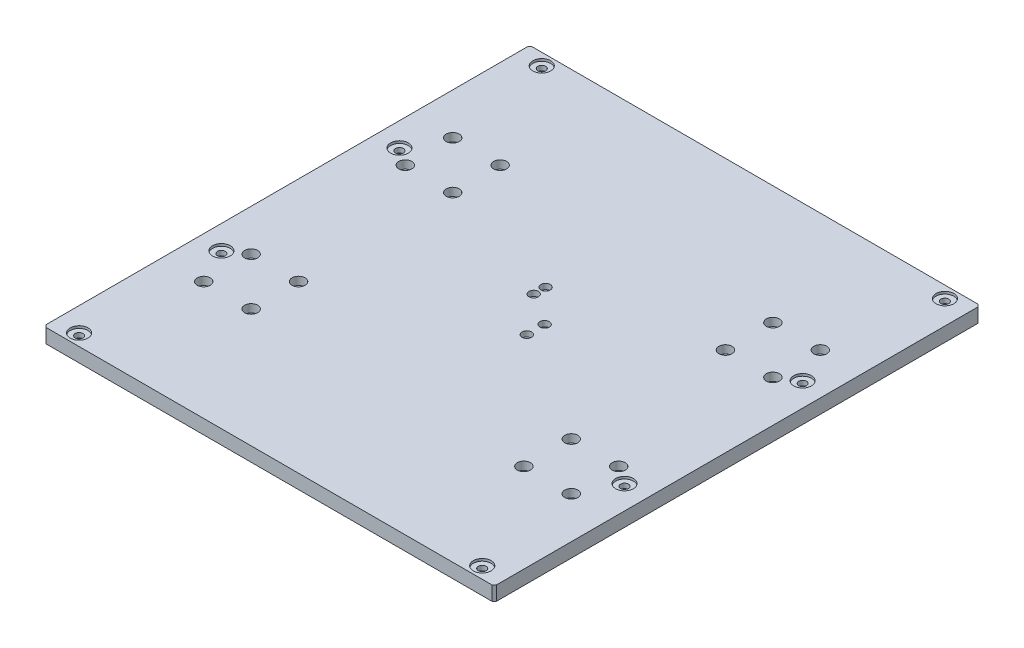
SolidWorks part; units mm, degrees
material "电木板A级"
ref_plane "前视" through (0, 0, 0) normal (0, 0, 1) x (1, 0, 0)
ref_plane "上视" through (0, 0, 0) normal (0, 1, 0) x (1, 0, 0)
ref_plane "右视" through (0, 0, 0) normal (1, 0, 0) x (0, 0, -1)
sketch "草图1" plane through (0, 0, 0) normal (0, 1, 0) x (1, 0, 0)
  line L1 (-190, -205) -> (190, -205)
  line L2 (-190, -205) -> (-190, 205)
  line L3 (-190, 205) -> (190, 205)
  line L4 (190, -205) -> (190, 205)
  line L5 (-190, -205) -> (190, 205) construction
  line L6 (-190, 205) -> (190, -205) construction
  point P0 (0, 0)
  dimension "D1" = 380
  dimension "D2" = 410
extrude "凸台-拉伸1" add sketch "草图1" along normal blind 12
hole_wizard "打孔尺寸根据内六角圆柱头螺钉的类型3" positions "草图3" profile "草图2" counterbore size "M6" standard "Gb" end condition through all
sketch "草图3" plane through (0, 12, 0) normal (0, 1, 0) x (1, 0, 0)
  line L0 (0, -205) -> (0, 0) construction
  line L1 (-190, -205) -> (190, -205) construction
  line L2 (0, 0) -> (190, 0) construction
  line L3 (190, -205) -> (190, 205) construction
  point P20 (-115, 65)
  point P21 (-115, 105)
  point P22 (-155, 105)
  point P23 (-155, 65)
  point P35 (155, 65)
  point P36 (155, 105)
  point P37 (115, 105)
  point P38 (115, 65)
  point P39 (115, -65)
  point P40 (115, -105)
  point P41 (155, -105)
  point P42 (155, -65)
  point P43 (-155, -65)
  point P44 (-155, -105)
  point P45 (-115, -105)
  point P46 (-115, -65)
  dimension "D1" = 40
  dimension "D2" = 40
  dimension "D3" = 270
  dimension "D4" = 130
sketch "草图2" plane through (-115, 12, -65) normal (1, 0, 0) x (0, 0, 1)
  line L0 (0, 0) -> (0, 12)
  line L1 (0, 12) -> (3.3, 12)
  line L3 (3.3, 12) -> (3.3, 6.8)
  line L4 (3.3, 6.8) -> (5.5, 6.8)
  line L5 (5.5, 6.8) -> (5.5, 0)
  line L7 (5.5, 0) -> (0, 0)
  line L11 (0, -6.35) -> (0, 107.95) construction
  dimension "通孔孔直径" = 6.6
  dimension "通孔孔深度" = 12
  dimension "柱形沉头孔直径" = 11
  dimension "柱形沉头孔深度" = 6.8
hole_wizard "打孔尺寸根据内六角圆柱头螺钉的类型3" positions "草图5" profile "草图4" counterbore size "M4" standard "Gb" end condition through all
sketch "草图5" plane through (0, 12, 0) normal (0, 1, 0) x (1, 0, 0)
  line L0 (38.9, 0) -> (190, 0) construction
  line L2 (-190, -205) -> (190, -205) construction
  line L3 (190, -205) -> (190, 205) construction
  line L4 (-190, -205) -> (190, -205) construction
  line L5 (190, -205) -> (190, 205) construction
  point P0 (20, 7.5)
  point P8 (20, -7.5)
  point P9 (0, -205)
  point P14 (190, 0)
  point P17 (-6.7, 25)
  point P21 (-6.7, 35)
  point P24 (0, -205)
  dimension "D1" = 15
  dimension "D2" = 20
  dimension "D3" = 25
  dimension "D4" = 6.7
  dimension "D5" = 10
sketch "草图4" plane through (20, 12, -7.5) normal (1, 0, 0) x (0, 0, 1)
  line L0 (0, 0) -> (0, 12)
  line L1 (0, 12) -> (2.25, 12)
  line L3 (2.25, 12) -> (2.25, 4.6)
  line L4 (2.25, 4.6) -> (4, 4.6)
  line L5 (4, 4.6) -> (4, 0)
  line L7 (4, 0) -> (0, 0)
  line L11 (0, -6.35) -> (0, 107.95) construction
  dimension "通孔孔直径" = 4.5
  dimension "通孔孔深度" = 12
  dimension "柱形沉头孔直径" = 8
  dimension "柱形沉头孔深度" = 4.6
hole_wizard "打孔尺寸根据内六角圆柱头螺钉的类型3" positions "草图9" profile "草图8" counterbore size "M6" standard "Gb" end condition through all
sketch "草图9" plane through (-174.7145, 0, 28.6293) normal (0, 1, 0) x (1, 0, 0)
  line L0 (174.7145, -176.3707) -> (174.7145, 28.6293) construction
  line L1 (-15.2855, -176.3707) -> (364.7145, -176.3707) construction
  line L2 (174.7145, 28.6293) -> (-15.2855, 28.6293) construction
  line L3 (-15.2855, 233.6293) -> (-15.2855, -176.3707) construction
  point P0 (4.7145, 223.7293)
  point P2 (4.7145, 103.7293)
  point P17 (344.7145, 103.7293)
  point P18 (344.7145, 223.7293)
  point P21 (344.7145, -166.4707)
  point P22 (344.7145, -46.4707)
  point P23 (4.7145, -46.4707)
  point P24 (4.7145, -166.4707)
  dimension "D1" = 340
  dimension "D2" = 120
  dimension "D3" = 150.2
sketch "草图8" plane through (-170, 0, -195.1) normal (1, 0, 0) x (0, 0, -1)
  line L0 (0, 0) -> (0, 12)
  line L1 (0, 12) -> (3.3, 12)
  line L3 (3.3, 12) -> (3.3, 6)
  line L4 (3.3, 6) -> (5.5, 6)
  line L5 (5.5, 6) -> (5.5, 0)
  line L7 (5.5, 0) -> (0, 0)
  line L11 (0, -6.35) -> (0, 107.95) construction
  dimension "通孔孔直径" = 6.6
  dimension "通孔孔深度" = 12
  dimension "柱形沉头孔直径" = 11
  dimension "柱形沉头孔深度" = 6
hole_wizard "孔1" positions "草图12" profile "草图11" legacy
sketch "草图12" plane through (0, 12, 0) normal (0, 1, 0) x (1, 0, 0)
  line L0 (0, 205) -> (0, -77.6062) construction
  line L1 (190, 205) -> (-190, 205) construction
  line L2 (-190, 0) -> (-50.1476, 0) construction
  line L3 (-190, 205) -> (-190, -205) construction
  point P0 (-170, 75.1)
  point P3 (-170, 195.1)
  point P22 (170, 195.1)
  point P23 (170, 75.1)
  point P30 (170, -75.1)
  point P31 (170, -195.1)
  point P32 (-170, -195.1)
  point P33 (-170, -75.1)
sketch "草图11" plane through (-170, 12, -75.1) normal (1, 0, 0) x (0, 0, 1)
  line L0 (0, 0) -> (0, 2)
  line L1 (0, 2) -> (7.5, 2)
  line L2 (7.5, 2) -> (7.5, 0)
  line L3 (7.5, 0) -> (0, 0)
  line L4 (0, 110) -> (0, -10) construction
  dimension "直径" = 15
  dimension "深度" = 2
chamfer "倒角1" distance 2 angle 45 4 edges at (-190, 6, -205) (190, 6, -205) (190, 6, 205) (-190, 6, 205)
